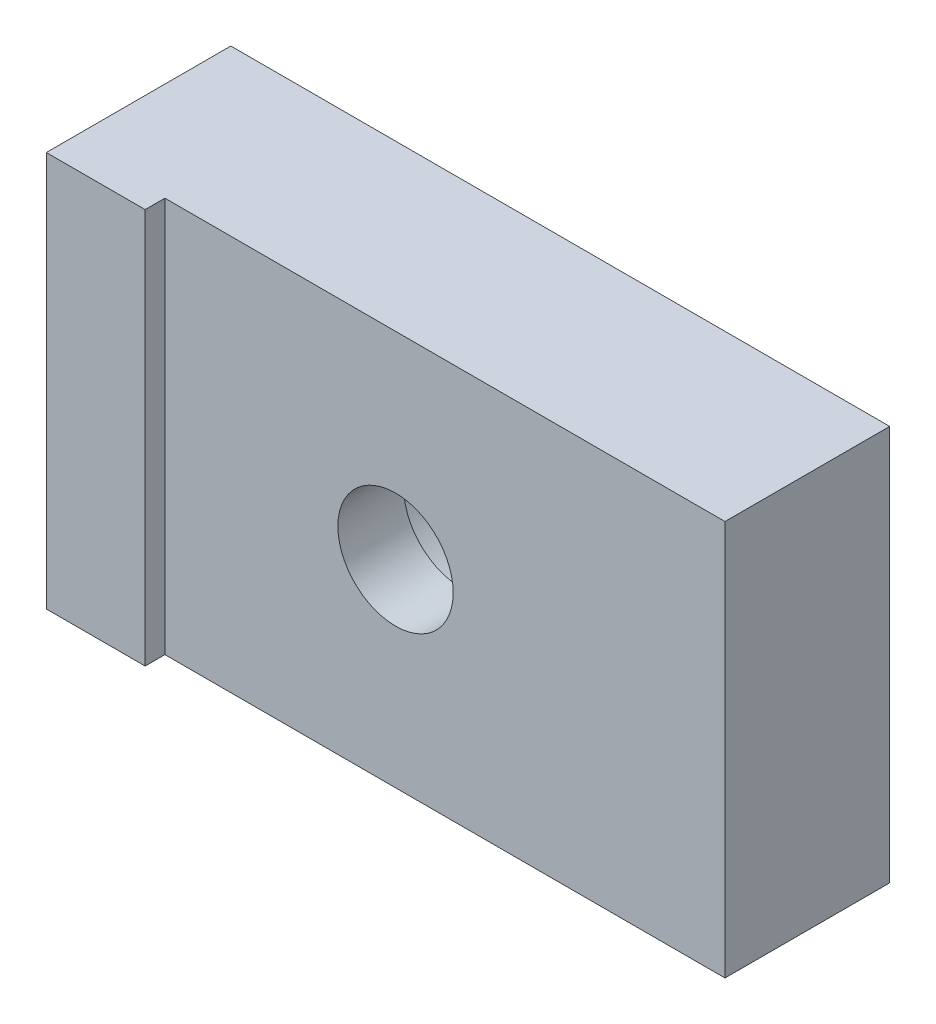
SolidWorks part; units mm, degrees
ref_plane "Front Plane" through (0, 0, 0) normal (0, 0, 1) x (1, 0, 0)
ref_plane "Top Plane" through (0, 0, 0) normal (0, 1, 0) x (1, 0, 0)
ref_plane "Right Plane" through (0, 0, 0) normal (1, 0, 0) x (0, 0, -1)
sketch "Sketch1" plane through (0, 0, 0) normal (0, 0, 1) x (1, 0, 0)
  line L0 (10, 12) -> (10, 6) construction
  line L1 (0, 0) -> (20, 0)
  line L2 (0, 0) -> (0, 12)
  line L3 (0, 12) -> (20, 12)
  line L4 (20, 0) -> (20, 12)
  line L5 (10, 6) -> (20, 6) construction
  circle A0 centre (10, 6) radius 1.75
  point P8 (10, 6)
  dimension "D3" = 3.5
  dimension "D1" = 20
  dimension "D2" = 12
extrude "Boss-Extrude1" add sketch "Sketch1" along normal blind 5
sketch "Sketch2" plane through (0, 0, 5) normal (0, 0, 1) x (1, 0, 0)
  line L0 (0, 0) -> (20, 0) construction
  line L1 (0, 12) -> (3, 12)
  line L2 (0, 12) -> (0, 0)
  line L3 (0, 0) -> (3, 0)
  line L4 (3, 12) -> (3, 0)
  dimension "D1" = 3
extrude "Boss-Extrude2" add sketch "Sketch2" along normal blind 0.6
sketch "Sketch3" plane through (0, 0, 0) normal (0, 0, -1) x (-1, 0, 0)
  circle A0 centre (-10, 6) radius 3
  dimension "D1" = 6
extrude "Cut-Extrude1" cut sketch "Sketch3" against normal blind 3
